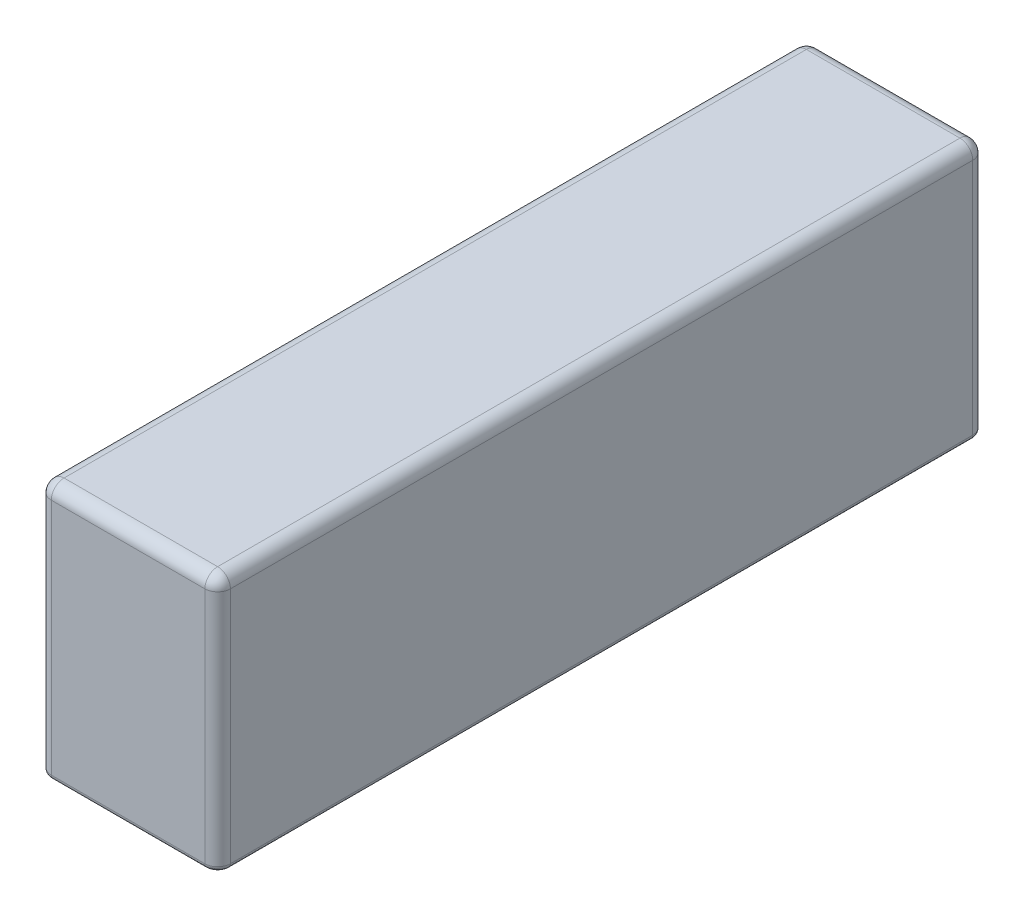
SolidWorks part; units mm, degrees
ref_plane "Front Plane" through (0, 0, 0) normal (0, 0, 1) x (1, 0, 0)
ref_plane "Top Plane" through (0, 0, 0) normal (0, 1, 0) x (1, 0, 0)
ref_plane "Right Plane" through (0, 0, 0) normal (1, 0, 0) x (0, 0, -1)
sketch "Sketch1" plane through (0, 0, 0) normal (0, 1, 0) x (1, 0, 0)
  line L1 (-3.5, -15) -> (3.5, -15)
  line L2 (-3.5, -15) -> (-3.5, 15)
  line L3 (-3.5, 15) -> (3.5, 15)
  line L4 (3.5, -15) -> (3.5, 15)
  line L5 (-3.5, -15) -> (3.5, 15) construction
  line L6 (-3.5, 15) -> (3.5, -15) construction
  point P0 (0, 0)
  dimension "D1" = 7
  dimension "D2" = 30
extrude "Boss-Extrude1" add sketch "Sketch1" along normal mid plane 10
fillet "Fillet1" radius 0.5 8 edges at (0, 5, 15) (-3.5, 5, 0) (0, 5, -15) (3.5, 5, 0) (-3.5, 0, -15) (3.5, 0, -15) (-3.5, 0, 15) (3.5, 0, 15)
fillet "Fillet2" radius 0.2 8 edges at (-3.3536, -5, 14.8536) (0, -5, 15) (3.3536, -5, 14.8536) (3.5, -5, 0) (3.3536, -5, -14.8536) (0, -5, -15) (-3.3536, -5, -14.8536) (-3.5, -5, 0)
